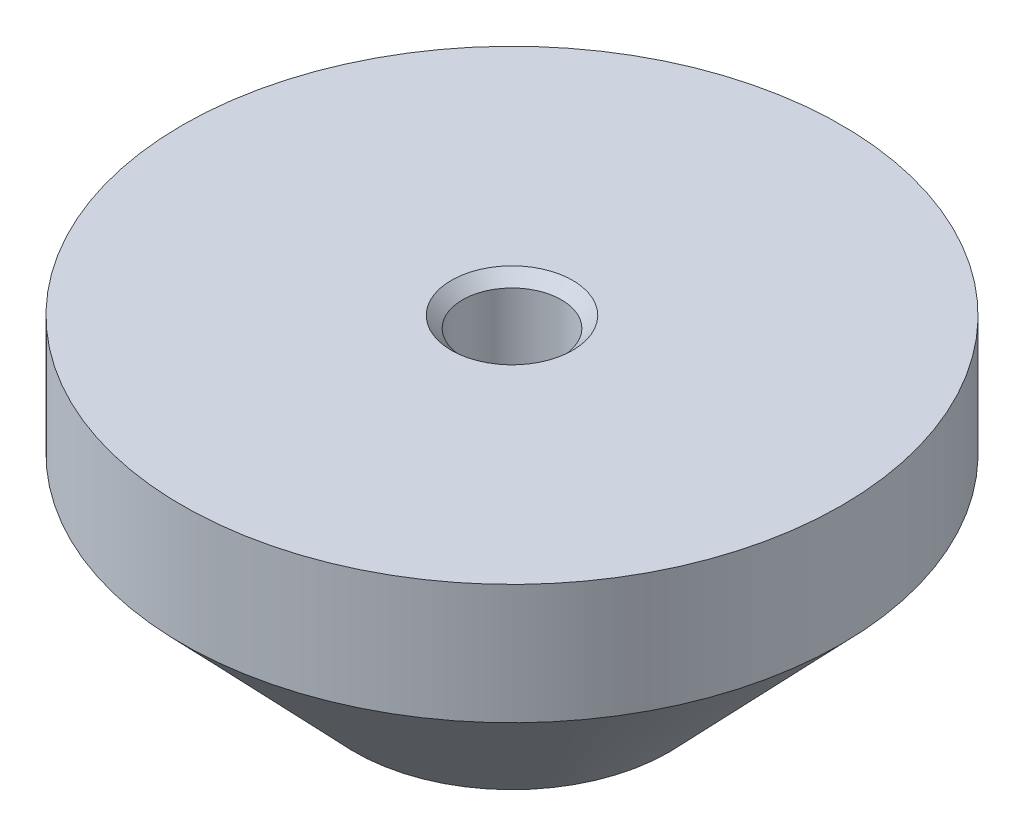
SolidWorks part; units mm, degrees
ref_plane "Front Plane" through (0, 0, 0) normal (0, 0, 1) x (1, 0, 0)
ref_plane "Top Plane" through (0, 0, 0) normal (0, 1, 0) x (1, 0, 0)
ref_plane "Right Plane" through (0, 0, 0) normal (1, 0, 0) x (0, 0, -1)
sketch "Sketch1" plane through (0, 0, 0) normal (0, 0, 1) x (1, 0, 0)
  line L0 (0, 0) -> (-11, 0)
  line L1 (-11, 0) -> (-11, -4)
  line L2 (-11, -4) -> (-5.25, -10)
  line L3 (-5.25, -10) -> (-4.5, -10)
  line L4 (-4.5, -10) -> (-4.5, -8.3)
  line L5 (-4.5, -8.3) -> (-4.2, -8.3)
  line L6 (0, -12.5) -> (0, 0)
  line L7 (-4.2, -8.3) -> (0, -8.3) construction
  line L8 (0, -8.3) -> (0, -12.5) construction
  arc A0 (-4.2, -8.3) -> (0, -12.5) centre (0, -8.3) ccw
  point P10 (-5.25, -10)
  point P11 (-11, -5.0524)
  dimension "D1" = 11
  dimension "D2" = 10
  dimension "D3" = 5.25
  dimension "D4" = 0.3
  dimension "D5" = 4.5
  dimension "D6" = 12.5
  dimension "D7" = 4
revolve "Revolve1" add sketch "Sketch1" angle 360 about L6
hole_wizard "M4x0.7 Tapped Hole1" positions "Sketch2" profile "Sketch3" tap size "M4x0.7" standard "ANSI Metric"
sketch "Sketch2" plane through (0, 0, 0) normal (0, 1, 0) x (1, 0, 0)
  point P0 (0, 0)
sketch "Sketch3" plane through (0, 0, 0) normal (1, 0, 0) x (0, 0, 1)
  line L0 (0, 0) -> (0, 7.5)
  line L1 (0, 7.5) -> (1.65, 6.5086)
  line L2 (1.65, 6.5086) -> (1.65, 0.375)
  line L3 (1.65, 0.375) -> (2.025, 0)
  line L5 (2.025, 0) -> (0, 0)
  line L6 (-1.65, 0.375) -> (-2.025, 0) construction
  line L10 (0, 7.5) -> (-1.65, 6.5086) construction
  line L11 (0, -6.35) -> (0, 107.95) construction
  dimension "Tap Drill Dia." = 3.3
  dimension "Tap Drill Depth" = 7.5
  dimension "Near C'Sink Dia." = 4.05
  dimension "Near C'Sink Angle" = 90
  dimension "Drill Angle" = 118
cosmetic thread "Hole Thread2" parameters "D1"=6, "D2"=4
equation "\"D3@Sketch1\"=10.5/2"
